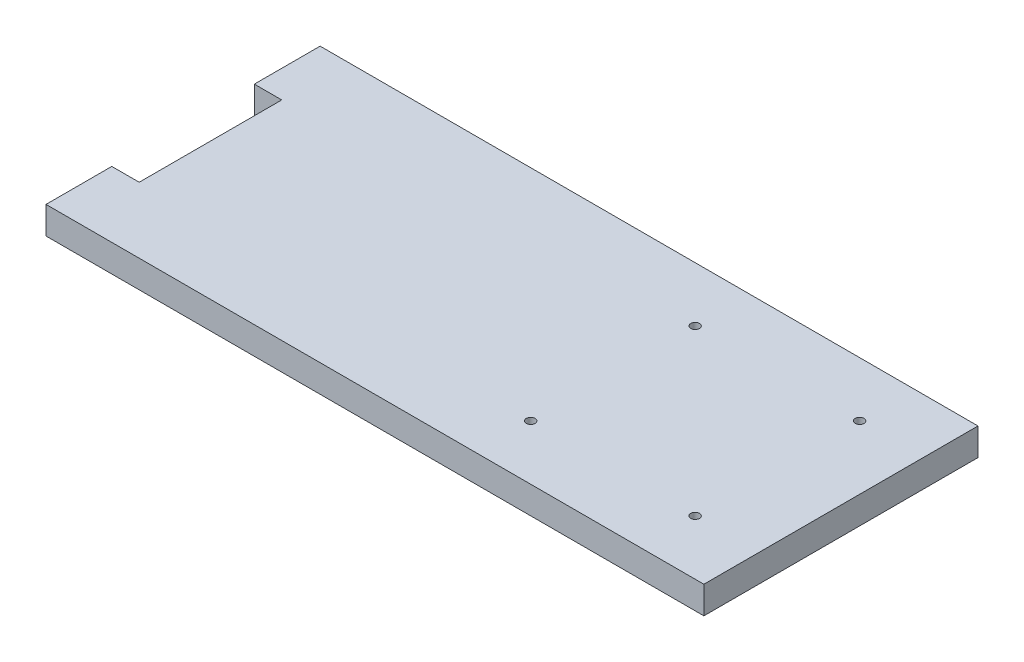
SolidWorks part; units mm, degrees
ref_plane "Front Plane" through (0, 0, 0) normal (0, 0, 1) x (1, 0, 0)
ref_plane "Top Plane" through (0, 0, 0) normal (0, 1, 0) x (1, 0, 0)
ref_plane "Right Plane" through (0, 0, 0) normal (1, 0, 0) x (0, 0, -1)
sketch "Sketch1" plane through (0, 0, 0) normal (0, 1, 0) x (1, 0, 0)
  line L1 (-38.1, 15.875) -> (38.1, 15.875)
  line L2 (-38.1, 15.875) -> (-38.1, -15.875)
  line L3 (-38.1, -15.875) -> (38.1, -15.875)
  line L4 (38.1, 15.875) -> (38.1, -15.875)
  line L5 (-38.1, 15.875) -> (38.1, -15.875) construction
  line L6 (-38.1, -15.875) -> (38.1, 15.875) construction
  point P0 (0, 0)
  dimension "D1" = 31.75
  dimension "D2" = 76.2
extrude "Boss-Extrude1" add sketch "Sketch1" along normal blind 3.175
sketch "Sketch2" plane through (0, 3.175, 0) normal (0, 1, 0) x (1, 0, 0)
  line L0 (-38.1, 15.875) -> (-38.1, -15.875) construction
  line L1 (-38.1, 8.255) -> (-34.925, 8.255)
  line L2 (-38.1, 8.255) -> (-38.1, -8.255)
  line L3 (-38.1, -8.255) -> (-34.925, -8.255)
  line L4 (-34.925, 8.255) -> (-34.925, -8.255)
  line L5 (38.1, 15.875) -> (-38.1, 15.875) construction
  line L6 (-38.1, -15.875) -> (38.1, -15.875) construction
  line L7 (0, 0) -> (38.1, 0) construction
  line L8 (38.1, -15.875) -> (38.1, 15.875) construction
  circle A0 centre (30.737, 9.525) radius 0.508
  circle A1 centre (30.737, -9.525) radius 0.508
  circle A2 centre (11.687, 9.525) radius 0.508
  circle A3 centre (11.687, -9.525) radius 0.508
  dimension "D4" = 6.35
  dimension "D1" = 7.62
  dimension "D2" = 7.62
  dimension "D3" = 3.175
  dimension "D5" = 19.05
  dimension "D6" = 19.05
  dimension "D7" = 6.35
  dimension "D8" = 19.05
  dimension "D9" = 6.35
extrude "Cut-Extrude1" cut sketch "Sketch2" against normal blind 3.175
